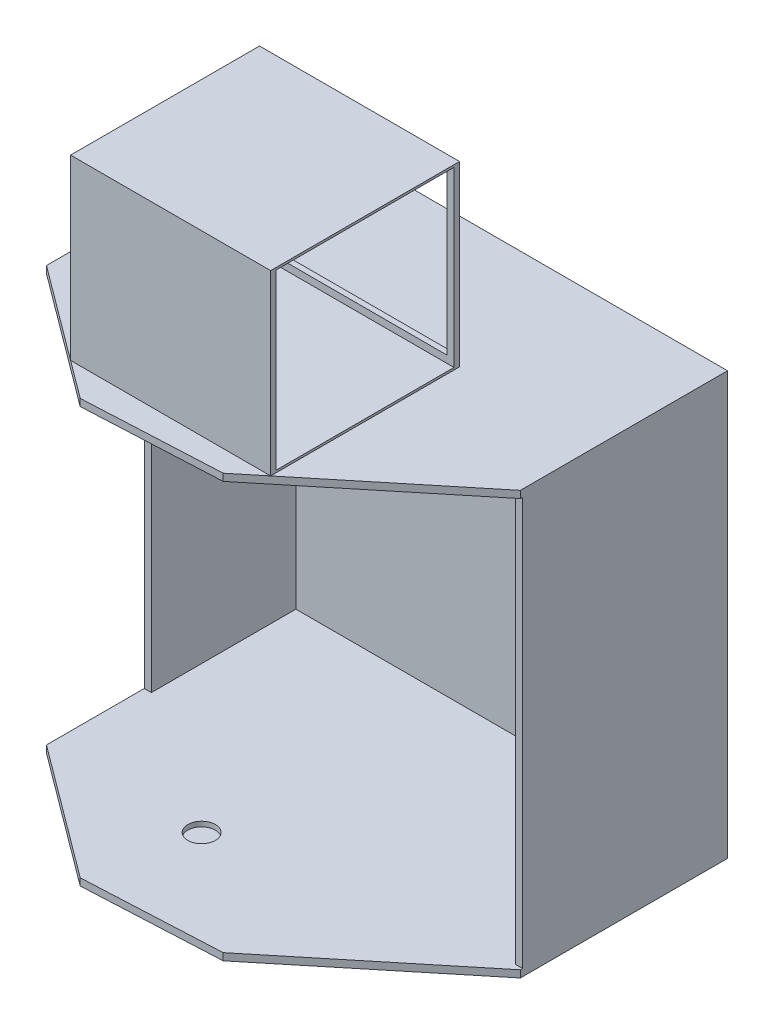
SolidWorks part; units mm, degrees
ref_plane "Front Plane" through (0, 0, 0) normal (0, 0, 1) x (1, 0, 0)
ref_plane "Top Plane" through (0, 0, 0) normal (0, 1, 0) x (1, 0, 0)
ref_plane "Right Plane" through (0, 0, 0) normal (1, 0, 0) x (0, 0, -1)
sketch "Sketch1" plane through (0, 0, 0) normal (0, 1, 0) x (1, 0, 0)
  line L0 (-71.1993, 0) -> (119.8007, 0)
  line L1 (119.8007, 0) -> (119.8007, -90)
  line L2 (119.8007, -90) -> (46.2729, -150.1553)
  line L3 (46.2729, -150.1553) -> (-15.0357, -153.1811)
  line L4 (-15.0357, -153.1811) -> (-74.3993, -109)
  line L5 (-74.3993, -109) -> (-74.3993, -65)
  line L6 (-74.3993, -65) -> (-71.1993, -65)
  line L7 (-71.1993, -65) -> (-71.1993, 0)
  dimension "D1" = 191
  dimension "D2" = 90
  dimension "D3" = 74
  dimension "D4" = 95
  dimension "D6" = 65
  dimension "D7" = 3.2
  dimension "D9" = 44
extrude "Boss-Extrude1" add sketch "Sketch1" along normal blind 3.2
sketch "Sketch3" plane through (0, 0, 0) normal (0, -1, 0) x (1, 0, 0)
  line L1 (-74.3993, 108.0683) -> (119.7657, 108.4369) construction
  line L2 (-74.3993, 65) -> (-74.3993, 109) construction
  line L3 (-5.3993, 152.7055) -> (-5.3993, 0) construction
  line L4 (-15.0357, 153.1811) -> (46.2729, 150.1553) construction
  line L5 (119.8007, 0) -> (-71.1993, 0) construction
  circle A0 centre (-5.3993, 108.1993) radius 12.3
  dimension "D3" = 24.6
  dimension "D1" = 45
  dimension "D2" = 69
extrude "Boss-Extrude2" add sketch "Sketch3" along normal blind 3.2
sketch "Sketch4" plane through (0, -3.2, 0) normal (0, -1, 0) x (1, 0, 0)
  circle A0 centre (-5.3993, 108.1993) radius 4
  dimension "D1" = 8
extrude "Boss-Extrude3" add sketch "Sketch4" along normal blind 4
sketch "Sketch6" plane through (0, 0, 0) normal (0, 1, 0) x (1, 0, 0)
  line L0 (-74.3993, -65) -> (-74.3993, 0)
  line L1 (-74.3993, 0) -> (-71.1993, 0)
  line L2 (-71.1993, 0) -> (-71.1993, -65)
  line L3 (-71.1993, -65) -> (-74.3993, -65)
extrude "Boss-Extrude4" add sketch "Sketch6" along normal blind 190
sketch "Sketch8" plane through (0, 0, 0) normal (0, 1, 0) x (1, 0, 0)
  line L0 (119.8007, 0) -> (116.6007, 0)
  line L1 (119.8007, 0) -> (-71.1993, 0) construction
  line L2 (116.6007, 0) -> (116.6007, -89)
  line L3 (116.6007, -89) -> (119.8007, -89)
  line L4 (119.8007, -90) -> (119.8007, 0) construction
  line L5 (119.8007, -89) -> (119.8007, 0)
  dimension "D1" = 3.2
  dimension "D2" = 89
extrude "Boss-Extrude5" add sketch "Sketch8" along normal blind 190
ref_plane "Plane2" through (0, 95, 0) normal (0, -1, 0) x (-1, 0, 0)
mirror "Mirror1" about plane through (0, 95, 0) normal (0, -1, 0) of "Boss-Extrude3", "Boss-Extrude1", "Boss-Extrude2"
sketch "Sketch9" plane through (0, 0, 0) normal (0, 0, 1) x (1, 0, 0)
  line L0 (22.7007, 190) -> (22.7007, 0) construction
  line L3 (-74.3993, 95) -> (119.8007, 95) construction
  line L4 (-74.3993, 186.8) -> (-74.3993, 3.2) construction
  line L5 (119.8007, 186.8) -> (119.8007, 3.2) construction
  line L6 (119.8007, 190) -> (-74.3993, 190) construction
  line L7 (119.8007, 0) -> (-74.3993, 0) construction
  line L8 (119.8007, 190) -> (119.8007, 0) construction
  line L9 (-74.3993, 0) -> (119.8007, 0)
  line L10 (-74.3993, 0) -> (-74.3993, 190)
  line L11 (-74.3993, 190) -> (119.8007, 190)
  line L12 (119.8007, 0) -> (119.8007, 190)
  line L13 (-74.3993, 0) -> (119.8007, 190) construction
  line L14 (-74.3993, 190) -> (119.8007, 0) construction
  point P12 (22.7007, 95)
extrude "Boss-Extrude7" add sketch "Sketch9" against normal blind 3.2
sketch "Sketch10" plane through (0, 3.2, 0) normal (0, 1, 0) x (1, 0, 0)
  circle A0 centre (-5.3993, -108.1993) radius 6.2
  dimension "D1" = 12.4
ref_plane "Plane3" through (0, 95, 0) normal (0, 1, 0) x (1, 0, 0)
sketch "Sketch11" plane through (0, 95, 0) normal (0, 1, 0) x (1, 0, 0)
  circle A0 centre (-5.3993, -108.1993) radius 6.2
extrude "Cut-Extrude2" cut sketch "Sketch11" against normal mid plane 188
sketch "Sketch12" plane through (0, 0, -3.2) normal (0, 0, -1) x (-1, 0, 0)
  line L0 (-22.7007, 190) -> (-22.7007, 0) construction
  line L1 (-119.8007, 190) -> (74.3993, 190) construction
  line L2 (74.3993, 0) -> (-119.8007, 0) construction
  line L3 (-119.8007, 95) -> (74.3993, 95) construction
  line L4 (-119.8007, 0) -> (-119.8007, 190) construction
  line L5 (74.3993, 190) -> (74.3993, 0) construction
  circle A0 centre (-22.7007, 95) radius 35
  dimension "D1" = 70
extrude "Boss-Extrude8" add sketch "Sketch12" along normal blind 20
sketch "Sketch14" plane through (0, 190, 0) normal (0, 1, 0) x (1, 0, 0)
  line L0 (-31.9964, -140.5581) -> (58.0036, -140.5581)
  line L1 (-74.3993, -109) -> (-15.0357, -153.1811) construction
  line L2 (46.2729, -150.1553) -> (119.8007, -90) construction
  line L3 (58.0036, -140.5581) -> (58.0036, -55.5581)
  line L4 (58.0036, -55.5581) -> (-31.9964, -55.5581)
  line L5 (-31.9964, -55.5581) -> (-31.9964, -140.5581)
  dimension "D1" = 90
  dimension "D2" = 85
extrude "Boss-Extrude9" add sketch "Sketch14" along normal blind 80
sketch "Sketch15" plane through (58.0036, 0, 0) normal (1, 0, 0) x (0, 0, -1)
  line L0 (-98.0581, 270) -> (-98.0581, 190) construction
  line L1 (-140.5581, 270) -> (-55.5581, 270) construction
  line L2 (-140.5581, 190) -> (-55.5581, 190) construction
  line L3 (-140.5581, 230) -> (-55.5581, 230) construction
  line L4 (-140.5581, 270) -> (-140.5581, 190) construction
  line L5 (-55.5581, 270) -> (-55.5581, 190) construction
  line L7 (-58.0581, 191) -> (-138.0581, 191)
  line L8 (-58.0581, 191) -> (-58.0581, 269)
  line L9 (-58.0581, 269) -> (-138.0581, 269)
  line L10 (-138.0581, 191) -> (-138.0581, 269)
  line L11 (-58.0581, 191) -> (-138.0581, 269) construction
  line L12 (-58.0581, 269) -> (-138.0581, 191) construction
  point P12 (-98.0581, 230)
  dimension "D1" = 78
  dimension "D2" = 80
extrude "Cut-Extrude3" cut sketch "Sketch15" against normal blind 88
sketch "Sketch16" plane through (0, 0, 58.0581) normal (0, 0, 1) x (1, 0, 0)
  line L0 (13.0036, 270) -> (13.0036, 190) construction
  line L1 (-31.9964, 270) -> (58.0036, 270) construction
  line L2 (-15.0357, 190) -> (46.2729, 190) construction
  line L3 (-31.9964, 230) -> (58.0036, 230) construction
  line L4 (-31.9964, 270) -> (-31.9964, 190) construction
  line L5 (58.0036, 270) -> (58.0036, 190) construction
  line L7 (54.9417, 194.2346) -> (-28.9346, 194.2346)
  line L8 (54.9417, 194.2346) -> (54.9417, 265.7654)
  line L9 (54.9417, 265.7654) -> (-28.9346, 265.7654)
  line L10 (-28.9346, 194.2346) -> (-28.9346, 265.7654)
  line L11 (54.9417, 194.2346) -> (-28.9346, 265.7654) construction
  line L12 (54.9417, 265.7654) -> (-28.9346, 194.2346) construction
  point P12 (13.0036, 230)
extrude "Cut-Extrude7" cut sketch "Sketch16" against normal blind 10
